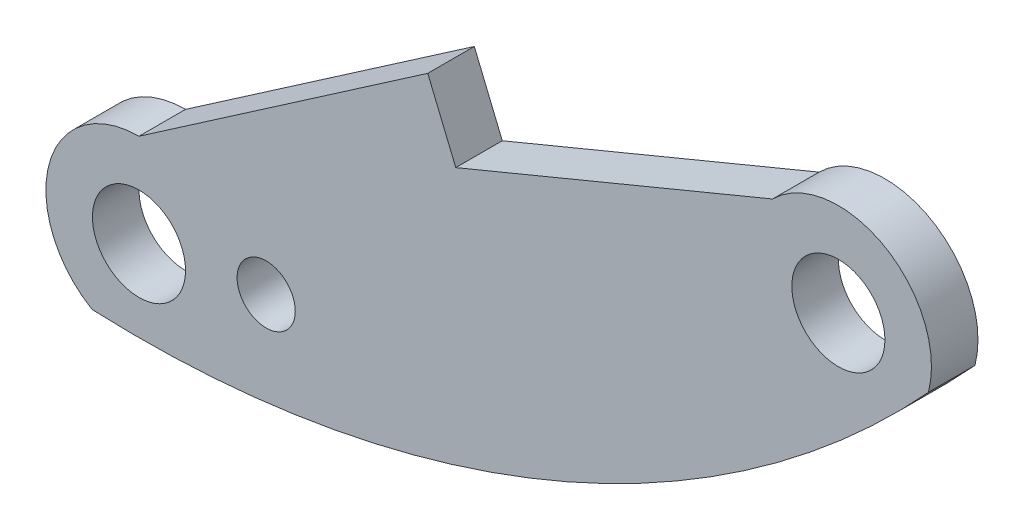
SolidWorks part; units mm, degrees
ref_plane "前视基准面" through (0, 0, 0) normal (0, 0, 1) x (1, 0, 0)
ref_plane "上视基准面" through (0, 0, 0) normal (0, 1, 0) x (1, 0, 0)
ref_plane "右视基准面" through (0, 0, 0) normal (1, 0, 0) x (0, 0, -1)
sketch "草图1" plane through (0, 0, 0) normal (0, 0, 1) x (1, 0, 0)
  line L0 (30.3111, -29.1816) -> (0.259, -41.6295) construction
  line L3 (0.259, -41.6295) -> (0.259, -56.6295) construction
  line L5 (15.2851, -35.4055) -> (10.049, -22.7645) construction
  line L8 (12.667, -29.085) -> (0.259, -37.6295)
  line L9 (15.2851, -35.4055) -> (16.4331, -38.1772) construction
  line L12 (27.4827, -26.3531) -> (13.8709, -31.9913)
  line L13 (13.8709, -31.9913) -> (12.667, -29.085)
  line L14 (16.4331, -38.1772) -> (6.2058, -42.4135) construction
  line L15 (6.2058, -42.4135) -> (5.724, -40.7832) construction
  circle A1 centre (0.259, -41.6295) radius 2
  circle A3 centre (30.3111, -29.1816) radius 2
  circle A5 centre (0.259, 0.8705) radius 46 construction
  arc A9 (-28.0878, -25.1816) -> (28.6059, -25.1816) centre (0.259, 0.8705) ccw construction
  circle A13 centre (30.3111, -29.1816) radius 4 construction
  circle A14 centre (0.259, -41.6295) radius 4 construction
  arc A15 (27.4827, -26.3531) -> (34.179, -30.201) centre (30.3111, -29.1816) cw
  arc A16 (0.259, -37.6295) -> (-1.7551, -45.0854) centre (0.259, -41.6295) ccw
  arc A18 (34.179, -30.201) -> (-1.7551, -45.0854) centre (0.259, 0.8705) cw
  circle A19 centre (15.2851, -35.4055) radius 1.5 construction
  circle A20 centre (5.724, -40.7832) radius 1.25
extrude "凸台-拉伸1" add sketch "草图1" along normal blind 2
sketch "草图2" plane through (0, 0, 0) normal (0, 0, -1) x (-1, 0, 0)
  circle A0 centre (-5.724, -40.7832) radius 1.5
sketch "草图3" plane through (0, 0, 2) normal (0, 0, 1) x (1, 0, 0)
  circle A0 centre (5.724, -40.7832) radius 1.5
